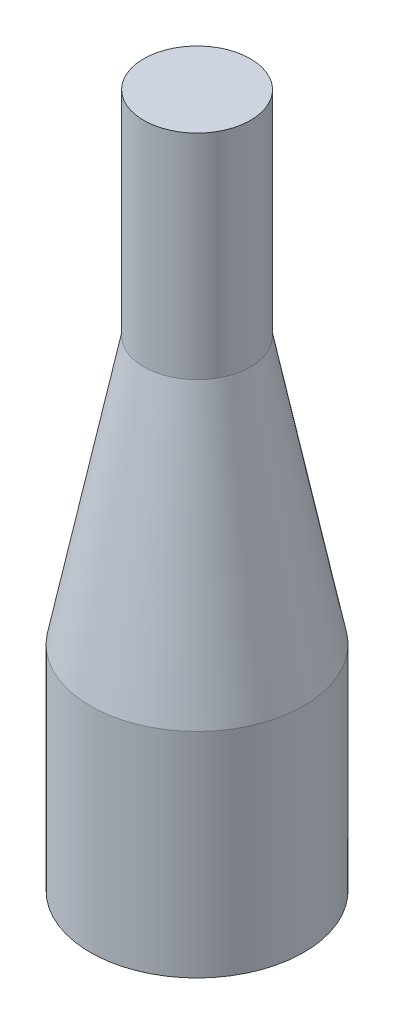
SolidWorks part; units mm, degrees
ref_plane "Front Plane" through (0, 0, 0) normal (0, 0, 1) x (1, 0, 0)
ref_plane "Top Plane" through (0, 0, 0) normal (0, 1, 0) x (1, 0, 0)
ref_plane "Right Plane" through (0, 0, 0) normal (1, 0, 0) x (0, 0, -1)
sketch "Sketch1" plane through (0, 0, 0) normal (0, 0, 1) x (1, 0, 0)
  line L0 (0, 0) -> (0, 101.6)
  line L1 (0, 0) -> (-50.8, 0)
  line L2 (-50.8, 0) -> (-50.8, 330.2) construction
  line L3 (-50.8, 330.2) -> (-25.4, 330.2)
  line L4 (-25.4, 330.2) -> (-25.4, 228.6)
  line L5 (-25.4, 228.6) -> (0, 101.6)
  line L6 (-27.94, 330.2) -> (-27.94, 228.6) construction
  line L7 (-2.54, 0) -> (-2.54, 101.6) construction
  line L8 (-27.94, 228.6) -> (-2.54, 101.6) construction
  line L9 (-50.8, 0) -> (-50.8, 330.2)
  point P11 (0, 0)
  dimension "D1" = 101.6
  dimension "D2" = 50.8
  dimension "D3" = 330.2
  dimension "D4" = 25.4
  dimension "D5" = 101.6
  dimension "D6" = 2.54
  dimension "D7" = 2.54
revolve "Revolve1" add sketch "Sketch1" angle 360 about L2
